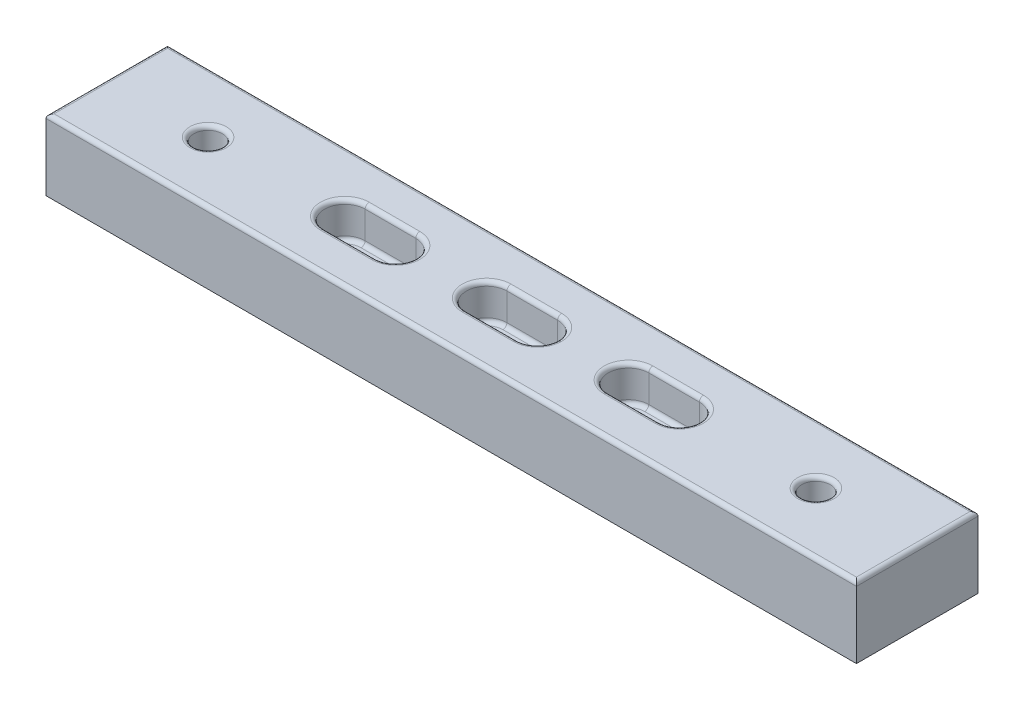
SolidWorks part; units mm, degrees
material "6061-T6 (SS)"
ref_plane "Front Plane" through (0, 0, 0) normal (0, 0, 1) x (1, 0, 0)
ref_plane "Top Plane" through (0, 0, 0) normal (0, 1, 0) x (1, 0, 0)
ref_plane "Right Plane" through (0, 0, 0) normal (1, 0, 0) x (0, 0, -1)
sketch "Sketch1" plane through (0, 0, 0) normal (0, 1, 0) x (1, 0, 0)
  line L1 (-200, -30) -> (200, -30)
  line L2 (-200, -30) -> (-200, 30)
  line L3 (-200, 30) -> (200, 30)
  line L4 (200, -30) -> (200, 30)
  line L5 (-200, -30) -> (200, 30) construction
  line L6 (-200, 30) -> (200, -30) construction
  point P0 (0, 0)
  dimension "D1" = 400
  dimension "D2" = 60
extrude "Boss-Extrude1" add sketch "Sketch1" along normal blind 35
sketch "Sketch2" plane through (0, 35, 0) normal (0, 1, 0) x (1, 0, 0)
  line L0 (200, -30) -> (200, 30) construction
  line L1 (200, 30) -> (-200, 30) construction
  line L2 (-200, 30) -> (-200, -30) construction
  circle A0 centre (-150, 0) radius 7
  circle A1 centre (150, 0) radius 7
  dimension "D1" = 14
  dimension "D2" = 14
  dimension "D3" = 50
  dimension "D4" = 30
  dimension "D5" = 50
  dimension "D6" = 30
extrude "Cut-Extrude1" cut sketch "Sketch2" against normal through all
hole_wizard "1/4-20 Tapped Hole1" positions "Sketch5" profile "Sketch6" tap size "1/4-20" standard "ANSI Inch"
sketch "Sketch5" plane through (0, 0, 0) normal (0, -1, 0) x (1, 0, 0)
  line L0 (-200, -30) -> (-200, 30) construction
  line L1 (-200, 30) -> (200, 30) construction
  line L2 (200, 30) -> (200, -30) construction
  point P2 (-168.77, 18.77)
  point P10 (-131.23, 18.77)
  point P12 (-131.23, -18.77)
  point P14 (-168.77, -18.77)
  point P19 (131.23, 18.77)
  point P21 (168.77, 18.77)
  point P23 (168.77, -18.77)
  point P25 (131.23, -18.77)
  dimension "D1" = 31.23
  dimension "D2" = 11.23
  dimension "D3" = 68.77
  dimension "D4" = 11.23
  dimension "D5" = 31.23
  dimension "D6" = 48.77
  dimension "D7" = 68.77
  dimension "D8" = 48.77
  dimension "D9" = 68.77
  dimension "D10" = 11.23
  dimension "D11" = 31.23
  dimension "D12" = 11.23
  dimension "D13" = 68.77
  dimension "D14" = 48.77
  dimension "D15" = 31.23
  dimension "D16" = 48.77
sketch "Sketch6" plane through (-168.77, 0, 18.77) normal (1, 0, 0) x (0, 0, -1)
  line L0 (0, 0) -> (0, 19.5338)
  line L1 (0, 19.5338) -> (2.5527, 18)
  line L2 (2.5527, 18) -> (2.5527, 1.2573)
  line L3 (2.5527, 1.2573) -> (3.81, 0)
  line L5 (3.81, 0) -> (0, 0)
  line L6 (-2.5527, 1.2573) -> (-3.81, 0) construction
  line L10 (0, 19.5338) -> (-2.5527, 18) construction
  line L11 (0, -6.35) -> (0, 107.95) construction
  dimension "Tap Drill Dia." = 5.1054
  dimension "Tap Drill Depth" = 18
  dimension "Near C'Sink Dia." = 7.62
  dimension "Near C'Sink Angle" = 90
  dimension "Drill Angle" = 118
cosmetic thread "Hole Thread1" parameters "D1"=12.7, "D2"=6.35
cosmetic thread "Hole Thread2" parameters "D1"=12.7, "D2"=6.35
cosmetic thread "Hole Thread3" parameters "D1"=12.7, "D2"=6.35
cosmetic thread "Hole Thread4" parameters "D1"=12.7, "D2"=6.35
cosmetic thread "Hole Thread5" parameters "D1"=12.7, "D2"=6.35
cosmetic thread "Hole Thread6" parameters "D1"=12.7, "D2"=6.35
cosmetic thread "Hole Thread7" parameters "D1"=12.7, "D2"=6.35
cosmetic thread "Hole Thread8" parameters "D1"=12.7, "D2"=6.35
sketch "Sketch7" plane through (0, 0, 0) normal (0, -1, 0) x (-1, 0, 0)
  line L0 (200, -30) -> (-200, -30) construction
  line L1 (30, 30) -> (-30, 30)
  line L2 (30, 30) -> (30, -30)
  line L3 (30, -30) -> (-30, -30)
  line L4 (-30, 30) -> (-30, -30)
  line L5 (30, 30) -> (-30, -30) construction
  line L6 (30, -30) -> (-30, 30) construction
  circle A0 centre (150, 0) radius 33.02
  circle A1 centre (-150, 0) radius 33.02
  point P6 (0, 0)
  dimension "D1" = 66.04
  dimension "D2" = 66.04
  dimension "D3" = 60
split line "Split Line1"
sketch "Sketch10" plane through (0, 35, 0) normal (0, 1, 0) x (1, 0, 0)
  line L0 (-200, 0) -> (200, 0) construction
  line L1 (-200, 30) -> (-200, -30) construction
  line L2 (200, -30) -> (200, 30) construction
  line L3 (57.5, 0) -> (82.5, 0) construction
  line L13 (-12.5, 0) -> (12.5, 0) construction
  line L14 (-12.5, 10) -> (12.5, 10)
  line L17 (-12.5, -10) -> (12.5, -10)
  line L18 (57.5, 10) -> (82.5, 10)
  line L19 (57.5, -10) -> (82.5, -10)
  line L20 (-12.5, 0) -> (57.5, 0) construction
  line L21 (-82.5, 0) -> (-57.5, 0) construction
  line L22 (-82.5, 10) -> (-57.5, 10)
  line L23 (-82.5, -10) -> (-57.5, -10)
  line L24 (-12.5, 0) -> (-82.5, 0) construction
  arc A14 (57.5, 10) -> (57.5, -10) centre (57.5, 0) ccw
  arc A17 (82.5, -10) -> (82.5, 10) centre (82.5, 0) ccw
  arc A18 (-12.5, 10) -> (-12.5, -10) centre (-12.5, 0) ccw
  arc A19 (12.5, -10) -> (12.5, 10) centre (12.5, 0) ccw
  arc A20 (-82.5, 10) -> (-82.5, -10) centre (-82.5, 0) ccw
  arc A21 (-57.5, -10) -> (-57.5, 10) centre (-57.5, 0) ccw
  point P8 (0, 0)
  point P13 (-22.5, 0)
  point P14 (22.5, 0)
  point P18 (70, 0)
  point P28 (-70, 0)
  dimension "D3" = 70
  dimension "D1" = 45
  dimension "D2" = 20
  dimension "D5" = 70
  dimension "D6" = 2
  dimension "D4" = 2
extrude "Cut-Extrude4" cut sketch "Sketch10" against normal blind 17.5
fillet "Fillet1" radius 2 30 edges at (0, 35, 30) (-200, 35, 0) (0, 35, -30) (200, 35, 0) (150, 35, 7) (-150, 35, 7) (22.5, 35, 0) (0, 35, -10) (-22.5, 35, 0) (0, 35, 10) (92.5, 35, 0) (70, 35, -10) (47.5, 35, 0) (70, 35, 10) (-47.5, 35, 0) (-70, 35, -10) (-92.5, 35, 0) (-70, 35, 10) (70, 17.5, -10) (92.5, 17.5, 0) (70, 17.5, 10) (47.5, 17.5, 0) (0, 17.5, -10) (22.5, 17.5, 0) (0, 17.5, 10) (-22.5, 17.5, 0) (-70, 17.5, -10) (-47.5, 17.5, 0) (-70, 17.5, 10) (-92.5, 17.5, 0)
equation "\"Crosshead Length\"= 400mm"
equation "\"Crosshead Width\"= 60mm"
equation "\"Height\"= 35mm"
equation "\"Screw Spacing\"= 300mm"
